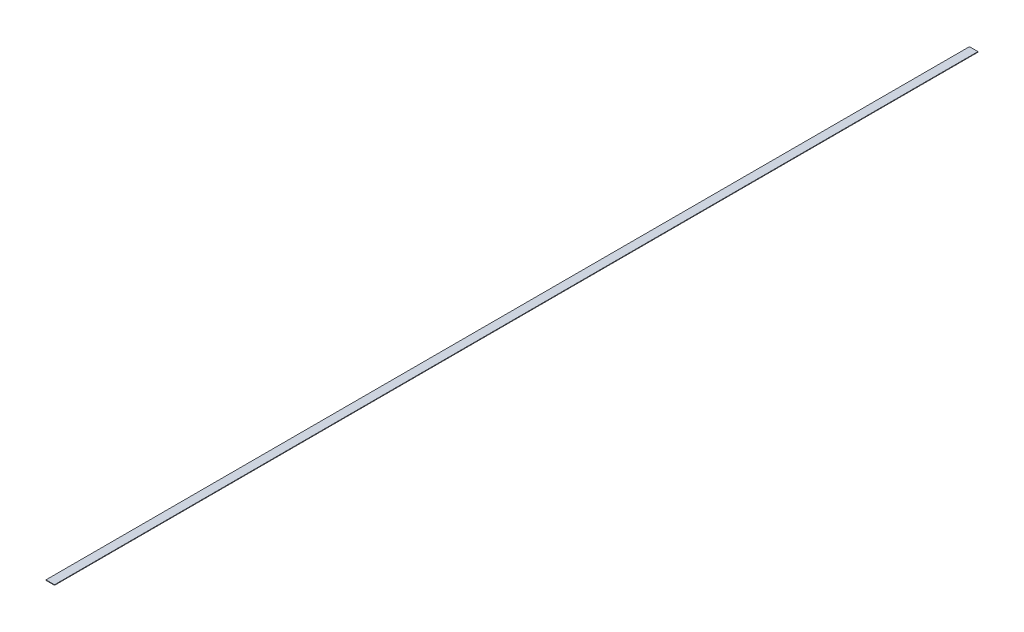
SolidWorks part; units mm, degrees
ref_plane "Front Plane" through (0, 0, 0) normal (0, 0, 1) x (1, 0, 0)
ref_plane "Top Plane" through (0, 0, 0) normal (0, 1, 0) x (1, 0, 0)
ref_plane "Right Plane" through (0, 0, 0) normal (1, 0, 0) x (0, 0, -1)
sketch "Sketch1" plane through (0, 0, 0) normal (0, 1, 0) x (1, 0, 0)
  line L1 (-25.4, -2746.375) -> (25.4, -2746.375)
  line L2 (-25.4, -2746.375) -> (-25.4, 2746.375)
  line L3 (-25.4, 2746.375) -> (25.4, 2746.375)
  line L4 (25.4, -2746.375) -> (25.4, 2746.375)
  line L5 (-25.4, -2746.375) -> (25.4, 2746.375) construction
  line L6 (-25.4, 2746.375) -> (25.4, -2746.375) construction
  point P0 (0, 0)
  dimension "D1" = 50.8
  dimension "D2" = 5492.75
extrude "Boss-Extrude1" add sketch "Sketch1" along normal blind 3.175
